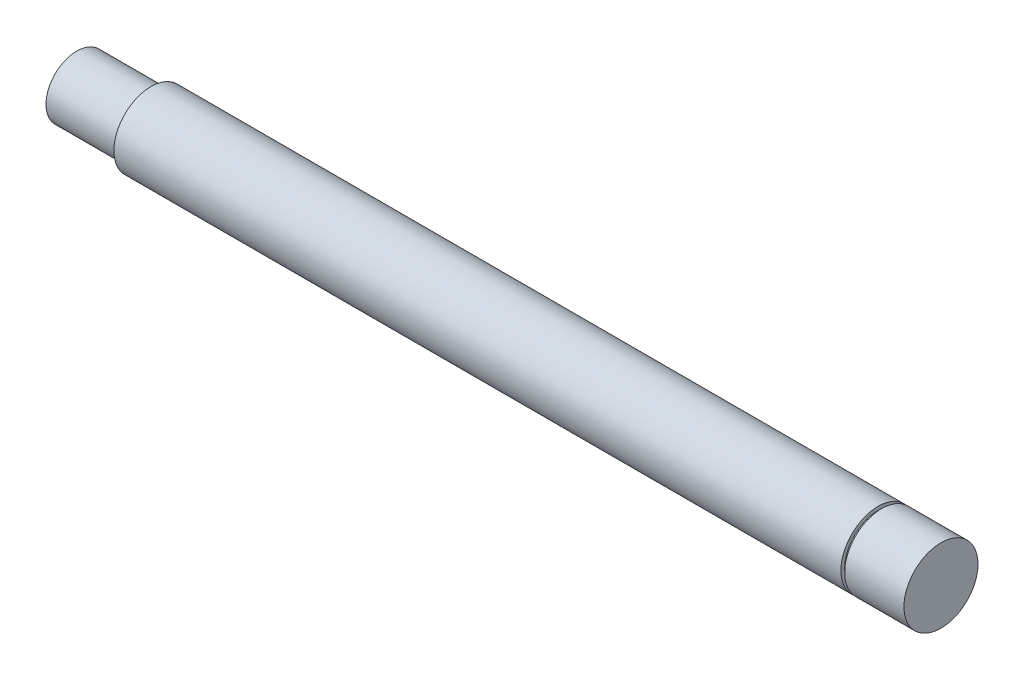
SolidWorks part; units mm, degrees
material "PW20:29:Sc:0:"
ref_plane "Front" through (0, 0, 0) normal (0, 0, 1) x (1, 0, 0)
ref_plane "Top" through (0, 0, 0) normal (0, 1, 0) x (1, 0, 0)
ref_plane "Right" through (0, 0, 0) normal (1, 0, 0) x (0, 0, -1)
other "Configuration Table"
sketch "Sketch1" plane through (0, 0, 0) normal (1, 0, 0) x (0, 0, -1)
  circle A0 centre (0, 0) radius 7.5
  dimension "D1" = 15
extrude "Base-Extrude" add sketch "Sketch1" along normal blind 175
ref_plane "Plane4" through (163, 0, 0) normal (1, 0, 0) x (0, 0, -1)
sketch "Sketch2" plane through (163, 0, 0) normal (1, 0, 0) x (0, 0, -1)
  circle A1 centre (0, 0) radius 6.75
  circle A2 centre (0, 0) radius 6.75
  circle A3 centre (0, 0) radius 7.5
  circle A4 centre (0, 0) radius 7.5
  dimension "D1" = 0.75
  dimension "D2" = 0
extrude "Cut-Extrude1" cut sketch "Sketch2" against normal blind 0.75
sketch "Sketch3" plane through (0, 0, 0) normal (-1, 0, 0) x (0, 0, 1)
  circle A0 centre (0, 0) radius 7.5 construction
  circle A1 centre (0, 0) radius 6.25
  circle A2 centre (0, 0) radius 6.25
  circle A3 centre (0, 0) radius 7.5
  dimension "D1" = 1.25
extrude "Cut-Extrude2" cut sketch "Sketch3" against normal blind 15
